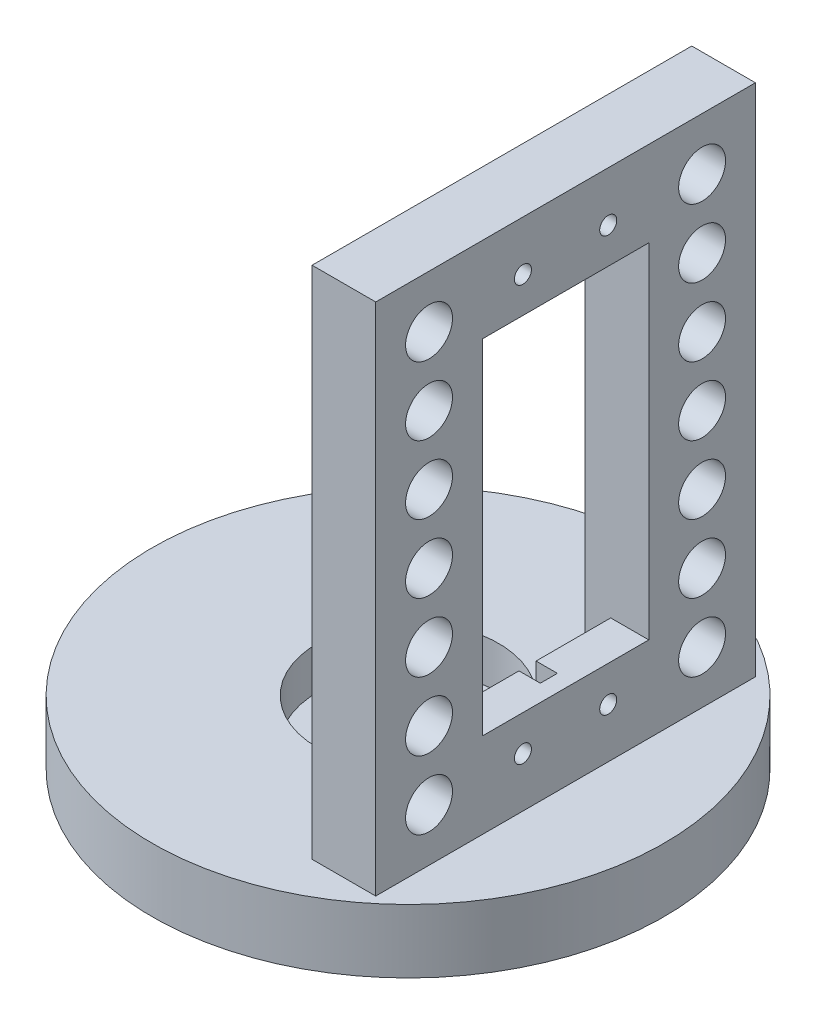
SolidWorks part; units mm, degrees
ref_plane "Front Plane" through (0, 0, 0) normal (0, 0, 1) x (1, 0, 0)
ref_plane "Top Plane" through (0, 0, 0) normal (0, 1, 0) x (1, 0, 0)
ref_plane "Right Plane" through (0, 0, 0) normal (1, 0, 0) x (0, 0, -1)
sketch "Sketch1" plane through (0, 0, 0) normal (0, 1, 0) x (1, 0, 0)
  line L0 (0, 20.731) -> (0, -22.0693) construction
  line L1 (-21.1032, 0) -> (21.8694, 0) construction
  circle A0 centre (0, 0) radius 30
  circle A1 centre (0, 0) radius 7 construction
  circle A2 centre (7, 0) radius 1
  circle A3 centre (0, -7) radius 1
  circle A4 centre (-7, 0) radius 1
  circle A5 centre (0, 7) radius 1
  circle A6 centre (0, 0) radius 4.9
  point P19 (0, 0)
  dimension "D1" = 60
  dimension "D2" = 2
  dimension "D3" = 14
  dimension "D5" = 9.8
  dimension "D4" = 4
extrude "Boss-Extrude1" add sketch "Sketch1" along normal blind 7.46
sketch "Sketch3" plane through (0, 7.46, 0) normal (0, 1, 0) x (1, 0, 0)
  line L0 (0, -30) -> (0, 30) construction
  line L1 (30, 0) -> (-30, 0) construction
  line L2 (11, 22.25) -> (11, -22.25)
  line L3 (11, -22.25) -> (18.46, -22.25)
  line L4 (18.46, -22.25) -> (18.46, 22.25)
  line L5 (11, 22.25) -> (18.46, 22.25)
  circle A0 centre (0, 0) radius 30 construction
  point P7 (18.46, 0)
  point P13 (11, 0)
  dimension "D1" = 7.46
  dimension "D2" = 11
  dimension "D3" = 22.25
extrude "Boss-Extrude2" add sketch "Sketch3" along normal blind 60.3
sketch "Sketch4" plane through (11, 0, 0) normal (-1, 0, 0) x (0, 0, 1)
  line L0 (0, 67.76) -> (0, 7.46) construction
  line L1 (-22.25, 67.76) -> (22.25, 67.76) construction
  line L2 (-22.25, 7.46) -> (22.25, 7.46) construction
  line L3 (-22.25, 57.76) -> (22.25, 57.76) construction
  line L4 (-22.25, 67.76) -> (-22.25, 7.46) construction
  line L5 (22.25, 67.76) -> (22.25, 7.46) construction
  line L6 (-22.25, 17.46) -> (22.25, 17.46) construction
  line L7 (-9.75, 67.76) -> (-9.75, 7.46) construction
  line L8 (9.75, 67.76) -> (9.75, 7.46) construction
  line L9 (-9.75, 37.61) -> (9.75, 37.61) construction
  line L10 (-9.75, 57.76) -> (9.75, 57.76)
  line L11 (-9.75, 57.76) -> (-9.75, 17.46)
  line L12 (-9.75, 17.46) -> (9.75, 17.46)
  line L13 (9.75, 57.76) -> (9.75, 17.46)
  circle A0 centre (-5, 61.93) radius 1
  circle A1 centre (5, 61.93) radius 1
  circle A2 centre (5, 13.29) radius 1
  circle A4 centre (-5, 13.29) radius 1
  dimension "D2" = 10
  dimension "D4" = 12.5
  dimension "D5" = 2
  dimension "D1" = 10
  dimension "D3" = 12.5
  dimension "D6" = 5
  dimension "D7" = 24.32
extrude "Cut-Extrude2" cut sketch "Sketch4" against normal through all
sketch "Sketch5" plane through (0, 7.46, 0) normal (0, 1, 0) x (1, 0, 0)
  circle A0 centre (0, 0) radius 10.6
  dimension "D1" = 21.2
extrude "Cut-Extrude3" cut sketch "Sketch5" against normal blind 4.96
sketch "Sketch6" plane through (11, 0, 0) normal (-1, 0, 0) x (0, 0, 1)
  line L0 (-22.25, 37.61) -> (22.25, 37.61) construction
  line L1 (-22.25, 67.76) -> (-22.25, 7.46) construction
  line L2 (22.25, 67.76) -> (22.25, 7.46) construction
  line L3 (0, 67.76) -> (0, 7.46) construction
  line L4 (-22.25, 67.76) -> (22.25, 67.76) construction
  line L5 (30, 7.46) -> (-30, 7.46) construction
  line L7 (-9.75, 64.61) -> (9.75, 64.61)
  line L8 (-9.75, 64.61) -> (-9.75, 10.61)
  line L9 (-9.75, 10.61) -> (9.75, 10.61)
  line L10 (9.75, 64.61) -> (9.75, 10.61)
  line L11 (-9.75, 64.61) -> (9.75, 10.61) construction
  line L12 (-9.75, 10.61) -> (9.75, 64.61) construction
  point P12 (0, 37.61)
  dimension "D1" = 54
  dimension "D2" = 19.5
extrude "Cut-Extrude4" cut sketch "Sketch6" against normal blind 3
sketch "Sketch7" plane through (14, 0, 0) normal (-1, 0, 0) x (0, 0, 1)
  line L0 (0, 64.61) -> (0, 10.61) construction
  line L1 (9.75, 64.61) -> (-9.75, 64.61) construction
  line L2 (-9.75, 10.61) -> (9.75, 10.61) construction
  line L3 (-9.75, 37.61) -> (9.75, 37.61) construction
  line L4 (-9.75, 64.61) -> (-9.75, 10.61) construction
  line L5 (9.75, 10.61) -> (9.75, 64.61) construction
  line L6 (-9.75, 61.185) -> (9.75, 61.185) construction
  line L7 (-9.75, 64.61) -> (-9.75, 57.76) construction
  line L8 (9.75, 57.76) -> (9.75, 64.61) construction
  line L9 (-9.75, 57.76) -> (9.75, 57.76) construction
  line L10 (-1, 64.61) -> (1, 64.61)
  line L11 (-1, 64.61) -> (-1, 57.76)
  line L12 (-1, 57.76) -> (1, 57.76)
  line L13 (1, 64.61) -> (1, 57.76)
  line L14 (-1, 64.61) -> (1, 57.76) construction
  line L15 (-1, 57.76) -> (1, 64.61) construction
  line L16 (-1, 17.46) -> (1, 10.61) construction
  line L17 (-1, 10.61) -> (1, 17.46) construction
  line L18 (1, 10.61) -> (1, 17.46)
  line L19 (-1, 17.46) -> (1, 17.46)
  line L20 (-1, 10.61) -> (-1, 17.46)
  line L21 (-1, 10.61) -> (1, 10.61)
  point P18 (0, 61.185)
  point P29 (0, 14.035)
  dimension "D1" = 2
extrude "Cut-Extrude5" cut sketch "Sketch7" against normal blind 2.5
sketch "Sketch8" plane through (11, 0, 0) normal (-1, 0, 0) x (0, 0, 1)
  line L0 (-22.25, 37.61) -> (-9.75, 37.61) construction
  line L1 (-22.25, 67.76) -> (-22.25, 7.46) construction
  line L2 (-9.75, 64.61) -> (-9.75, 10.61) construction
  line L3 (-16, 37.61) -> (-16, 67.76) construction
  line L4 (-22.25, 67.76) -> (22.25, 67.76) construction
  line L5 (0, 67.76) -> (0, 7.46) construction
  line L6 (-22.25, 7.46) -> (22.25, 7.46) construction
  circle A0 centre (-16, 37.61) radius 2.75
  circle A1 centre (-16, 45.61) radius 2.75
  circle A2 centre (-16, 53.61) radius 2.75
  circle A3 centre (-16, 61.61) radius 2.75
  circle A4 centre (-16, 13.61) radius 2.75
  circle A5 centre (-16, 21.61) radius 2.75
  circle A6 centre (-16, 29.61) radius 2.75
  circle A7 centre (16, 29.61) radius 2.75
  circle A8 centre (16, 21.61) radius 2.75
  circle A9 centre (16, 13.61) radius 2.75
  circle A10 centre (16, 61.61) radius 2.75
  circle A11 centre (16, 53.61) radius 2.75
  circle A12 centre (16, 45.61) radius 2.75
  circle A13 centre (16, 37.61) radius 2.75
  dimension "D1" = 5.5
  dimension "D3" = 8
  dimension "D2" = 4
extrude "Cut-Extrude6" cut sketch "Sketch8" against normal through all
